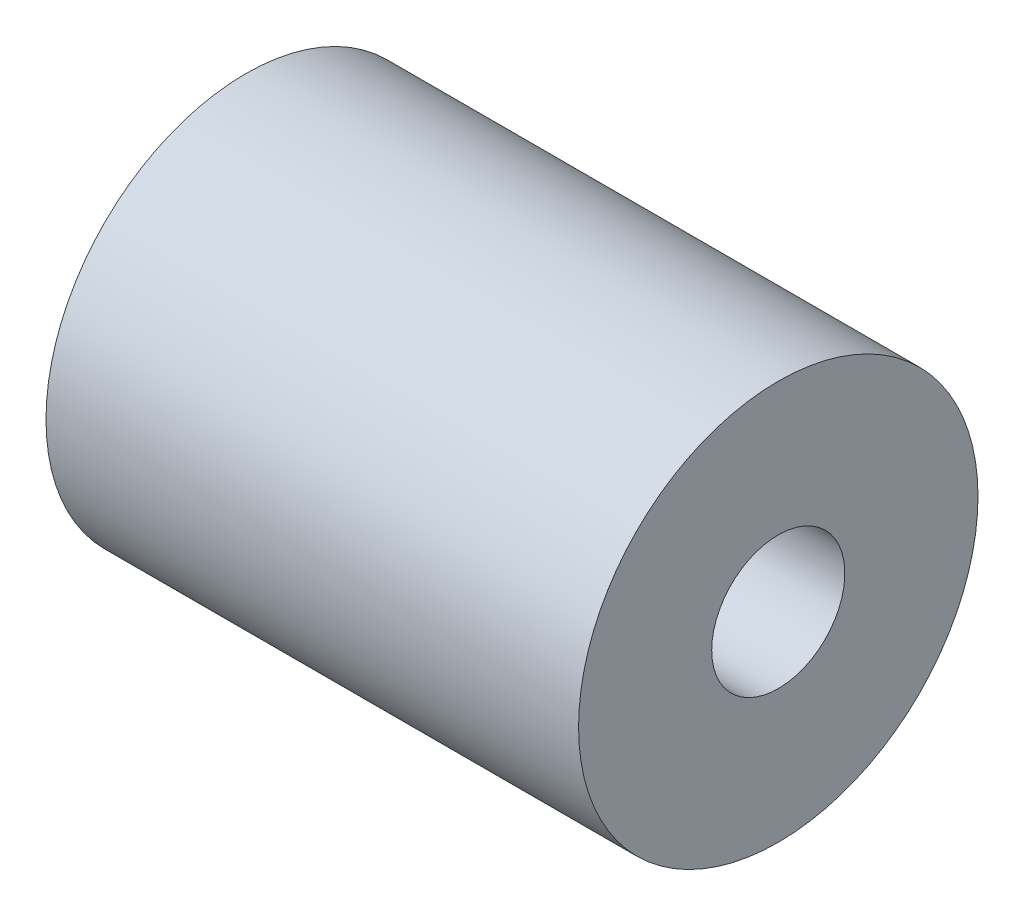
SolidWorks part; units mm, degrees
ref_plane "Front Plane" through (0, 0, 0) normal (0, 0, 1) x (1, 0, 0)
ref_plane "Top Plane" through (0, 0, 0) normal (0, 1, 0) x (1, 0, 0)
ref_plane "Right Plane" through (0, 0, 0) normal (1, 0, 0) x (0, 0, -1)
sketch "Sketch1" plane through (0, 0, 0) normal (1, 0, 0) x (0, 0, -1)
  circle A0 centre (0, 0) radius 9.525
  circle A1 centre (0, 0) radius 3.175
  dimension "D1" = 19.05
  dimension "D2" = 6.35
extrude "Boss-Extrude1" add sketch "Sketch1" along normal blind 25.4
